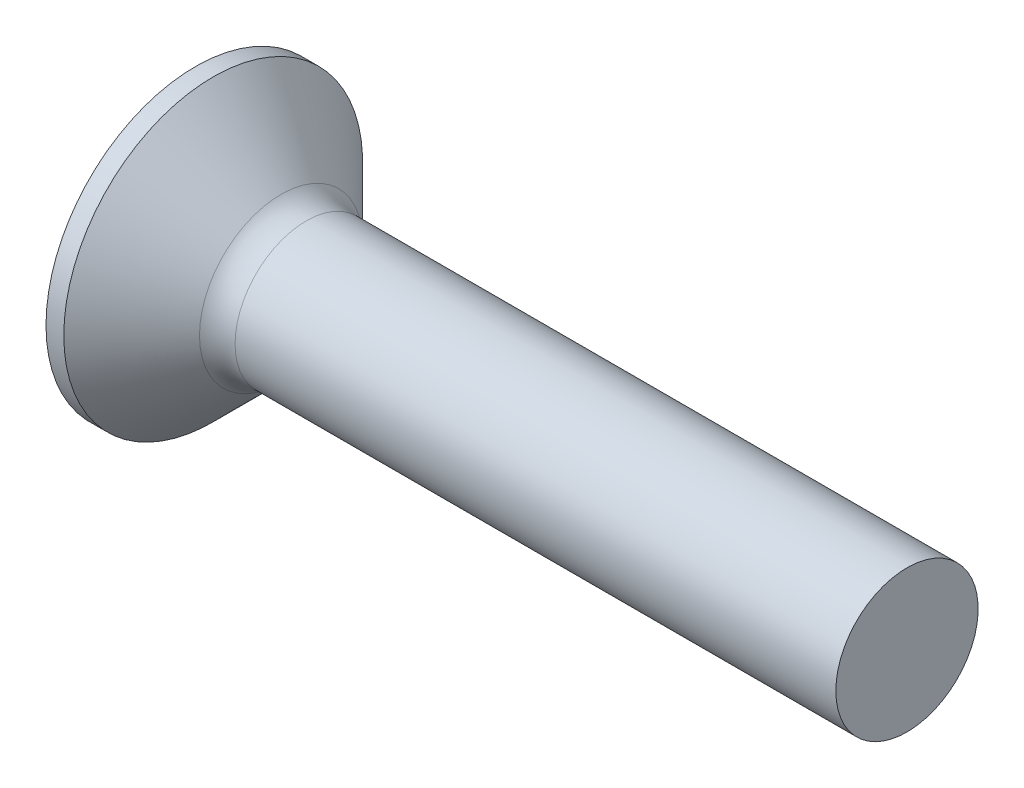
SolidWorks part; units mm, degrees
revolve "Base-Revolve" add sketch "BodySke" angle 360 about L5
sketch "BodySke" plane through (0, 0, 0) normal (0, 0, 1) x (1, 0, 0)
  line L0 (0, 0) -> (0, 4.2)
  line L1 (0, 4.2) -> (0.5, 4.2)
  line L2 (2.7, 2) -> (20, 2)
  line L3 (20, 2) -> (20, 0)
  line L4 (20, 0) -> (0, 0)
  line L5 (-6.35, 0) -> (82.55, 0) construction
  line L6 (2.7, -2) -> (20, -2) construction
  line L7 (0.5, -4.2) -> (2.7, -2) construction
  line L8 (0.5, 4.2) -> (2.7, 2)
  line L9 (0, -4.2) -> (0.5, -4.2) construction
  line L10 (3.4, 3.5875) -> (3.4, -5.9375) construction
  line L11 (0, 6.35) -> (0, -3.175) construction
  dimension "Diameter" = 4
  dimension "Length" = 20
  dimension "Head_ht" = 2.7
  dimension "Head_dia" = 8.4
  dimension "Head_ang" = 90
  dimension "D6" = 0.5
  dimension "Advance" = 0.7
  dimension "Thread_nom" = 20
cosmetic thread "ThreadCosmetic" [suppressed] parameters "Thread_length"=16.6, "Thread_minor"=3.22
ref_plane "Plane1" through (0, 0, 0) normal (0, 0, 1) x (1, 0, 0)
ref_plane "Plane2" through (0, 0, 0) normal (0, 1, 0) x (1, 0, 0)
ref_plane "Plane3" through (0, 0, 0) normal (1, 0, 0) x (0, 0, -1)
fillet "Fillet1" radius 1 1 edges at (2.7, 0, 2)
sketch "Sketch3" plane through (0, 0, 0) normal (-1, 0, 0) x (0, 0, 1)
  line L0 (-0.515, 2.2) -> (0.515, 2.2)
  line L1 (0.515, 2.2) -> (0.515, -2.2)
  line L2 (0.515, -2.2) -> (-0.515, -2.2)
  line L3 (-0.515, -2.2) -> (-0.515, 2.2)
  dimension "Cross_dia" = 4.4
  dimension "Cross_width" = 1.03
  dimension "D1" = 2.2
  dimension "D2" = 0.515
ref_plane "Plane4" through (2.51, 0, 0) normal (-1, 0, 0) x (0, 0, 1)
sketch "Sketch4" plane through (2.51, 0, 0) normal (-1, 0, 0) x (0, 0, 1)
  line L0 (-0.515, 0.9486) -> (0.515, 0.9486)
  line L3 (0.515, 0.9486) -> (0.515, -0.9486)
  line L4 (0.515, -0.9486) -> (-0.515, -0.9486)
  line L5 (-0.515, -0.9486) -> (-0.515, 0.9486)
  dimension "D2" = 1.8971
  dimension "D1" = 1.03
  dimension "D4" = 0.9486
  dimension "D3" = 0.515
loft "Recess" cut profiles "Sketch3", "Sketch4"
pattern_circular "RecPat" count 2 every 90 about axis through (0, 0, 0) along (1, 0, 0) of "Recess"
sketch "RecCorSke" plane through (0, 0, 0) normal (0, 0, 1) x (1, 0, 0)
  line L0 (-3.175, 0) -> (15.875, 0) construction
  line L2 (0, 0) -> (0, 1.0265)
  line L3 (0, 1.0265) -> (2.51, 0.851)
  line L4 (2.51, 0.851) -> (2.7865, 0)
  line L5 (2.7865, 0) -> (0, 0)
  dimension "Diameter" = 1.702
  dimension "Depth" = 2.51
  dimension "Draft_angle" = 4
  dimension "Bottom_angle" = 18
revolve "RecessCore" cut sketch "RecCorSke" angle 360 about L0
sketch "ThdSchSke" plane through (0, 0, 0) normal (0, 0, 1) x (1, 0, 0)
  line L0 (3.4, -1.61) -> (3.1269, -2)
  line L1 (3.4, -1.61) -> (3.6731, -2)
  line L2 (3.6731, -2) -> (3.6731, -2.5)
  line L3 (-3.175, 0) -> (5.1513, 0) construction
  line L5 (3.6731, -2.5) -> (3.1269, -2.5)
  line L6 (3.1269, -2.5) -> (3.1269, -2)
  line L7 (0, 4.2) -> (0, -4.2) construction
  dimension "Diameter" = 4
  dimension "Thread_minor" = 3.22
  dimension "Start" = 3.4
revolve "ThreadSchematic" [suppressed] cut sketch "ThdSchSke" angle 360 about L3
pattern_linear "ThdSchPat" [suppressed]
equation "\"D1@Sketch3\" = \"Cross_dia@Sketch3\" / 2"
equation "\"D2@Sketch3\" = \"Cross_width@Sketch3\" / 2"
equation "\"Depth@RecCorSke\" = \"Cross_depth@Plane4\""
equation "\"D1@Sketch4\" = \"Cross_width@Sketch3\""
equation "\"D2@Sketch4\" = \"Cross_dia@Sketch3\" - 2.0 * \"Cross_depth@Plane4\" * tan(26.5  * 0.017453292)"
equation "\"D3@Sketch4\" = \"D1@Sketch4\" / 2"
equation "\"D4@Sketch4\" = \"D2@Sketch4\" / 2"
equation "\"Thread_length@ThreadCosmetic\" = ((sgn( (\"Length@BodySke\" - \"Advance@BodySke\" * 1.0 - \"Head_ht@BodySke\" ) - \"Thread_nom@BodySke\" )-1)*( (\"Length@BodySke\" - \"Advance@BodySke\" * 1.0 - \"Head_ht@BodySke\" ) - \"Thread_nom@BodySke\" ))/-2+ \"Thread_nom@BodySke\""
equation "\"Thread_minor@ThdSchSke\" = \"Thread_minor@ThreadCosmetic\""
equation "\"Diameter@ThdSchSke\" = \"Diameter@BodySke\""
equation "\"Overcut@ThdSchSke\" = \"Diameter@BodySke\" * 1.25"
equation "\"Start@ThdSchSke\" = 0.000001 + \"Length@BodySke\" - \"Thread_length@ThreadCosmetic\"  '---Countersunk---"
equation "\"Num_threads@ThdSchPat\" = int( \"Thread_length@ThreadCosmetic\" / \"Advance@BodySke\" + 0.999 )  + 1"
equation "\"Advance@ThdSchPat\" = \"Thread_length@ThreadCosmetic\" /  (\"Num_threads@ThdSchPat\" - 1) 'relax it"
